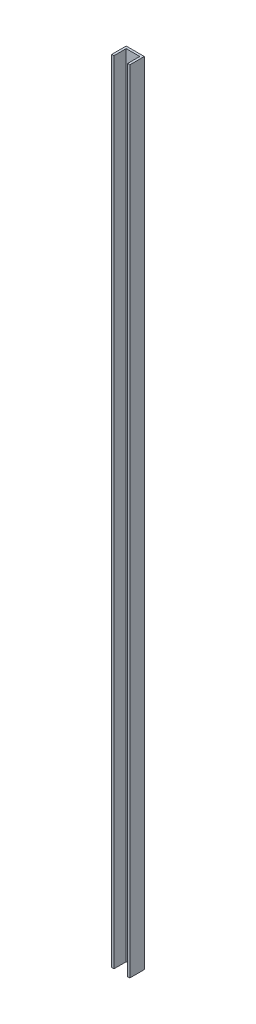
SolidWorks part; units mm, degrees
ref_plane "Front Plane" through (0, 0, 0) normal (0, 0, 1) x (1, 0, 0)
ref_plane "Top Plane" through (0, 0, 0) normal (0, 1, 0) x (1, 0, 0)
ref_plane "Right Plane" through (0, 0, 0) normal (1, 0, 0) x (0, 0, -1)
sketch "Sketch1" plane through (0, 0, 0) normal (0, 1, 0) x (1, 0, 0)
  line L0 (3.75, 2.75) -> (3.75, -4)
  line L1 (-5, 4) -> (5, 4)
  line L2 (-5, 4) -> (-5, -4)
  line L3 (-5, -4) -> (-3.75, -4)
  line L4 (5, 4) -> (5, -4)
  line L5 (-5, 4) -> (5, -4) construction
  line L6 (-5, -4) -> (5, 4) construction
  line L7 (-3.75, 2.75) -> (3.75, 2.75)
  line L8 (-3.75, 2.75) -> (-3.75, -4)
  line L9 (3.75, -4) -> (5, -4)
  point P0 (0, 0)
  dimension "D1" = 8
  dimension "D2" = 10
  dimension "D3" = 1.25
extrude "Boss-Extrude1" add sketch "Sketch1" along normal blind 436
